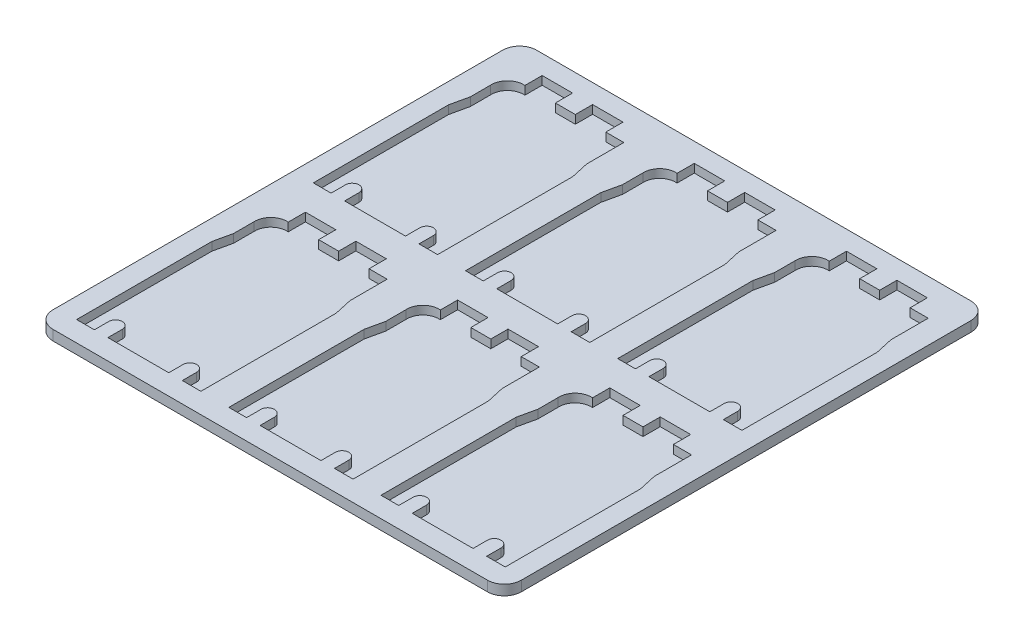
SolidWorks part; units mm, degrees
ref_plane "Front Plane" through (0, 0, 0) normal (0, 0, 1) x (1, 0, 0)
ref_plane "Top Plane" through (0, 0, 0) normal (0, 1, 0) x (1, 0, 0)
ref_plane "Right Plane" through (0, 0, 0) normal (1, 0, 0) x (0, 0, -1)
sketch "Sketch1" plane through (0, 0, 0) normal (0, 1, 0) x (1, 0, 0)
  line L1 (10, 0) -> (267, 0)
  line L2 (0, 10) -> (0, 276)
  line L3 (10, 286) -> (267, 286)
  line L4 (277, 10) -> (277, 276)
  arc A0 (267, 286) -> (277, 276) centre (267, 276) cw
  arc A1 (277, 10) -> (267, 0) centre (267, 10) cw
  arc A2 (10, 0) -> (0, 10) centre (10, 10) cw
  arc A3 (0, 276) -> (10, 286) centre (10, 276) cw
  point P11 (0, 0)
  dimension "D1" = 10
  dimension "D2" = 266
  dimension "D3" = 257
extrude "Boss-Extrude1" add sketch "Sketch1" along normal blind 6
sketch "Sketch2" plane through (0, 6, 0) normal (0, 1, 0) x (1, 0, 0)
  line L0 (12, 12) -> (22.5, 12)
  line L5 (30.5, 12) -> (66.5, 12)
  line L6 (74.5, 12) -> (85.5, 12)
  line L7 (12, 12) -> (12, 92)
  line L8 (85.5, 12) -> (85.5, 92)
  line L9 (12, 92) -> (14.3405, 102.5)
  line L10 (14.3405, 102.5) -> (14.3405, 114.5)
  line L11 (42.6595, 124.5) -> (54.4595, 124.5)
  line L12 (85.5, 92) -> (83.1595, 102.5)
  line L13 (83.1595, 102.5) -> (83.1595, 124.5)
  line L14 (22.5, 12) -> (22.5, 20.5)
  line L15 (30.5, 12) -> (30.5, 20.5)
  line L16 (66.5, 12) -> (66.5, 20.5)
  line L17 (74.5, 12) -> (74.5, 20.5)
  line L18 (0, 276) -> (0, 10) construction
  line L19 (10, 0) -> (267, 0) construction
  line L20 (72.4595, 124.5) -> (83.1595, 124.5)
  line L23 (24.6595, 134.6635) -> (42.6595, 134.6635)
  line L24 (42.6595, 124.5) -> (42.6595, 134.6635)
  line L26 (54.4595, 124.5) -> (54.4595, 134.7)
  line L27 (54.4595, 134.7) -> (72.4595, 134.7)
  line L28 (72.4595, 124.5) -> (72.4595, 134.7)
  line L30 (24.6595, 124.4635) -> (24.6595, 134.6635)
  line L31 (114.6595, 124.4635) -> (114.6595, 134.6635)
  line L32 (114.6595, 134.6635) -> (132.6595, 134.6635)
  line L33 (132.6595, 124.5) -> (132.6595, 134.6635)
  line L34 (132.6595, 124.5) -> (144.4595, 124.5)
  line L35 (144.4595, 124.5) -> (144.4595, 134.7)
  line L36 (144.4595, 134.7) -> (162.4595, 134.7)
  line L37 (162.4595, 124.5) -> (162.4595, 134.7)
  line L38 (162.4595, 124.5) -> (173.1595, 124.5)
  line L39 (173.1595, 102.5) -> (173.1595, 124.5)
  line L40 (175.5, 92) -> (173.1595, 102.5)
  line L41 (175.5, 12) -> (175.5, 92)
  line L42 (164.5, 12) -> (175.5, 12)
  line L43 (164.5, 12) -> (164.5, 20.5)
  line L44 (156.5, 12) -> (156.5, 20.5)
  line L45 (120.5, 12) -> (156.5, 12)
  line L46 (120.5, 12) -> (120.5, 20.5)
  line L47 (112.5, 12) -> (112.5, 20.5)
  line L48 (102, 12) -> (112.5, 12)
  line L49 (102, 12) -> (102, 92)
  line L50 (102, 92) -> (104.3405, 102.5)
  line L51 (104.3405, 102.5) -> (104.3405, 114.5)
  line L52 (204.6595, 124.4635) -> (204.6595, 134.6635)
  line L53 (204.6595, 134.6635) -> (222.6595, 134.6635)
  line L54 (222.6595, 124.5) -> (222.6595, 134.6635)
  line L55 (222.6595, 124.5) -> (234.4595, 124.5)
  line L56 (234.4595, 124.5) -> (234.4595, 134.7)
  line L57 (234.4595, 134.7) -> (252.4595, 134.7)
  line L58 (252.4595, 124.5) -> (252.4595, 134.7)
  line L59 (252.4595, 124.5) -> (263.1595, 124.5)
  line L60 (263.1595, 102.5) -> (263.1595, 124.5)
  line L61 (265.5, 92) -> (263.1595, 102.5)
  line L62 (265.5, 12) -> (265.5, 92)
  line L63 (254.5, 12) -> (265.5, 12)
  line L64 (254.5, 12) -> (254.5, 20.5)
  line L65 (246.5, 12) -> (246.5, 20.5)
  line L66 (210.5, 12) -> (246.5, 12)
  line L67 (210.5, 12) -> (210.5, 20.5)
  line L68 (202.5, 12) -> (202.5, 20.5)
  line L69 (192, 12) -> (202.5, 12)
  line L70 (192, 12) -> (192, 92)
  line L71 (192, 92) -> (194.3405, 102.5)
  line L72 (194.3405, 102.5) -> (194.3405, 114.5)
  line L73 (114.6595, 264.4635) -> (114.6595, 274.6635)
  line L74 (114.6595, 274.6635) -> (132.6595, 274.6635)
  line L75 (132.6595, 264.5) -> (132.6595, 274.6635)
  line L76 (132.6595, 264.5) -> (144.4595, 264.5)
  line L77 (144.4595, 264.5) -> (144.4595, 274.7)
  line L78 (144.4595, 274.7) -> (162.4595, 274.7)
  line L79 (162.4595, 264.5) -> (162.4595, 274.7)
  line L80 (162.4595, 264.5) -> (173.1595, 264.5)
  line L81 (173.1595, 242.5) -> (173.1595, 264.5)
  line L82 (175.5, 232) -> (173.1595, 242.5)
  line L83 (175.5, 152) -> (175.5, 232)
  line L84 (164.5, 152) -> (175.5, 152)
  line L85 (164.5, 152) -> (164.5, 160.5)
  line L86 (156.5, 152) -> (156.5, 160.5)
  line L87 (120.5, 152) -> (156.5, 152)
  line L88 (120.5, 152) -> (120.5, 160.5)
  line L89 (112.5, 152) -> (112.5, 160.5)
  line L90 (102, 152) -> (112.5, 152)
  line L91 (102, 152) -> (102, 232)
  line L92 (102, 232) -> (104.3405, 242.5)
  line L93 (104.3405, 242.5) -> (104.3405, 254.5)
  line L94 (204.6595, 264.4635) -> (204.6595, 274.6635)
  line L95 (204.6595, 274.6635) -> (222.6595, 274.6635)
  line L96 (222.6595, 264.5) -> (222.6595, 274.6635)
  line L97 (222.6595, 264.5) -> (234.4595, 264.5)
  line L98 (234.4595, 264.5) -> (234.4595, 274.7)
  line L99 (234.4595, 274.7) -> (252.4595, 274.7)
  line L100 (252.4595, 264.5) -> (252.4595, 274.7)
  line L101 (252.4595, 264.5) -> (263.1595, 264.5)
  line L102 (263.1595, 242.5) -> (263.1595, 264.5)
  line L103 (265.5, 232) -> (263.1595, 242.5)
  line L104 (265.5, 152) -> (265.5, 232)
  line L105 (254.5, 152) -> (265.5, 152)
  line L106 (254.5, 152) -> (254.5, 160.5)
  line L107 (246.5, 152) -> (246.5, 160.5)
  line L108 (210.5, 152) -> (246.5, 152)
  line L109 (210.5, 152) -> (210.5, 160.5)
  line L110 (202.5, 152) -> (202.5, 160.5)
  line L111 (192, 152) -> (202.5, 152)
  line L112 (192, 152) -> (192, 232)
  line L113 (192, 232) -> (194.3405, 242.5)
  line L114 (194.3405, 242.5) -> (194.3405, 254.5)
  line L115 (24.6595, 264.4635) -> (24.6595, 274.6635)
  line L116 (24.6595, 274.6635) -> (42.6595, 274.6635)
  line L117 (42.6595, 264.5) -> (42.6595, 274.6635)
  line L118 (42.6595, 264.5) -> (54.4595, 264.5)
  line L119 (54.4595, 264.5) -> (54.4595, 274.7)
  line L120 (54.4595, 274.7) -> (72.4595, 274.7)
  line L121 (72.4595, 264.5) -> (72.4595, 274.7)
  line L122 (72.4595, 264.5) -> (83.1595, 264.5)
  line L123 (83.1595, 242.5) -> (83.1595, 264.5)
  line L124 (85.5, 232) -> (83.1595, 242.5)
  line L125 (85.5, 152) -> (85.5, 232)
  line L126 (74.5, 152) -> (85.5, 152)
  line L127 (74.5, 152) -> (74.5, 160.5)
  line L128 (66.5, 152) -> (66.5, 160.5)
  line L129 (30.5, 152) -> (66.5, 152)
  line L130 (30.5, 152) -> (30.5, 160.5)
  line L131 (22.5, 152) -> (22.5, 160.5)
  line L132 (12, 152) -> (22.5, 152)
  line L133 (12, 152) -> (12, 232)
  line L134 (12, 232) -> (14.3405, 242.5)
  line L135 (14.3405, 242.5) -> (14.3405, 254.5)
  arc A2 (24.6595, 124.4635) -> (14.3405, 114.5) centre (23.8273, 115) ccw
  arc A3 (22.5, 20.5) -> (30.5, 20.5) centre (26.5, 20.5) cw
  arc A4 (66.5, 20.5) -> (74.5, 20.5) centre (70.5, 20.5) cw
  arc A5 (156.5, 20.5) -> (164.5, 20.5) centre (160.5, 20.5) cw
  arc A6 (112.5, 20.5) -> (120.5, 20.5) centre (116.5, 20.5) cw
  arc A7 (114.6595, 124.4635) -> (104.3405, 114.5) centre (113.8273, 115) ccw
  arc A8 (246.5, 20.5) -> (254.5, 20.5) centre (250.5, 20.5) cw
  arc A9 (202.5, 20.5) -> (210.5, 20.5) centre (206.5, 20.5) cw
  arc A10 (204.6595, 124.4635) -> (194.3405, 114.5) centre (203.8273, 115) ccw
  arc A11 (156.5, 160.5) -> (164.5, 160.5) centre (160.5, 160.5) cw
  arc A12 (112.5, 160.5) -> (120.5, 160.5) centre (116.5, 160.5) cw
  arc A13 (114.6595, 264.4635) -> (104.3405, 254.5) centre (113.8273, 255) ccw
  arc A14 (246.5, 160.5) -> (254.5, 160.5) centre (250.5, 160.5) cw
  arc A15 (202.5, 160.5) -> (210.5, 160.5) centre (206.5, 160.5) cw
  arc A16 (204.6595, 264.4635) -> (194.3405, 254.5) centre (203.8273, 255) ccw
  arc A17 (66.5, 160.5) -> (74.5, 160.5) centre (70.5, 160.5) cw
  arc A18 (22.5, 160.5) -> (30.5, 160.5) centre (26.5, 160.5) cw
  arc A19 (24.6595, 264.4635) -> (14.3405, 254.5) centre (23.8273, 255) ccw
  point P20 (83.1702, 102.4518)
  point P21 (13.1702, 97.25)
  dimension "D3" = 4
  dimension "D10" = 9.5
  dimension "D17" = 18
  dimension "D2" = 8.5
  dimension "D4" = 80
  dimension "D5" = 10.5
  dimension "D6" = 73.5
  dimension "D7" = 70
  dimension "D8" = 12
  dimension "D9" = 22
  dimension "D11" = 58.5
  dimension "D12" = 10.5
  dimension "D13" = 12
  dimension "D14" = 12
  dimension "D15" = 36
  dimension "D16" = 10.2
  dimension "D18" = 10.2
  dimension "D19" = 18
  dimension "D20" = 10.7
  dimension "D21" = 3
  dimension "D22" = 2
extrude "Cut-Extrude1" cut sketch "Sketch2" against normal blind 5
